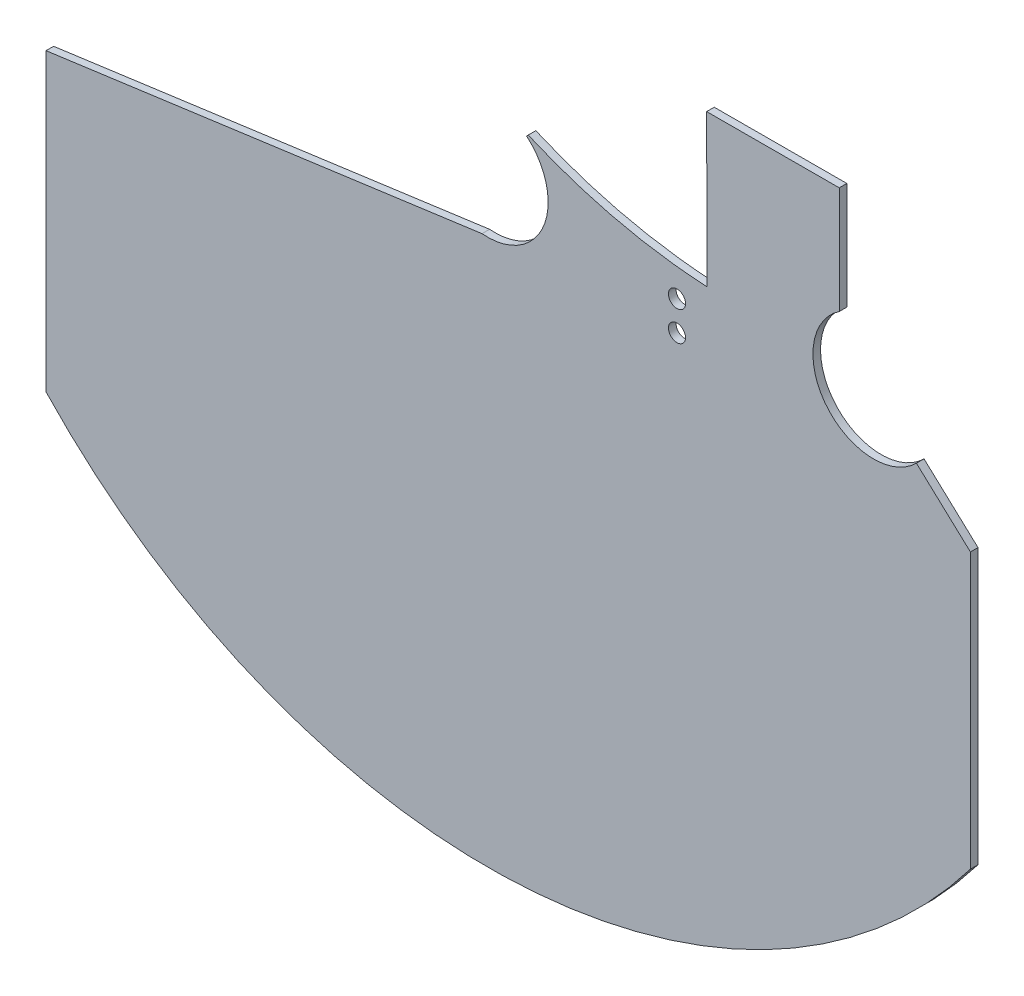
SolidWorks part; units mm, degrees
ref_plane "Front Plane" through (0, 0, 0) normal (0, 0, 1) x (1, 0, 0)
ref_plane "Top Plane" through (0, 0, 0) normal (0, 1, 0) x (1, 0, 0)
ref_plane "Right Plane" through (0, 0, 0) normal (1, 0, 0) x (0, 0, -1)
sketch "Sketch1" plane through (0, 0, 0) normal (0, 0, 1) x (1, 0, 0)
  line L0 (-76.8109, -42.6812) -> (-191.8981, -58.3949)
  line L2 (17.5303, -13.2779) -> (17.466, 14.9412)
  line L3 (-75.0109, -183.6853) -> (-75.0109, -185.6853) construction
  line L5 (-17.534, 14.8615) -> (17.466, 14.9412)
  line L6 (-65.0722, -14.4943) -> (-64.624, -14.0461)
  line L7 (-17.534, 14.8615) -> (-17.4429, -25.1385)
  line L8 (10.3223, 13.4067) -> (7.9165, -10.5732) construction
  line L9 (-83.9257, -51.7428) -> (-126.8973, -177.1633) construction
  line L10 (9.3388, 13.4067) -> (7.549, -10.599) construction
  line L11 (8.3498, 13.4067) -> (7.1746, -10.6299) construction
  line L12 (7.3501, 13.4067) -> (6.7894, -10.6662) construction
  line L13 (-75.305, -51.5878) -> (-75.0109, -180.7466) construction
  line L14 (-75.305, -51.5878) -> (-75.0109, -180.7466) construction
  line L15 (11.2975, 13.4067) -> (8.2735, -10.552) construction
  line L16 (12.2657, 13.4067) -> (8.6199, -10.5347) construction
  line L17 (13.2282, 13.4067) -> (8.9559, -10.5209) construction
  line L18 (14.1861, 13.4067) -> (9.2817, -10.5103) construction
  line L19 (15.1406, 13.4067) -> (9.5974, -10.5024) construction
  line L20 (16.0929, 13.4067) -> (11.113, -5.8245) construction
  line L21 (16.369, 11.049) -> (10.1986, -10.4939) construction
  line L22 (-75.305, -51.5878) -> (-75.0109, -180.7466) construction
  line L23 (16.369, 8.2303) -> (10.4845, -10.4926) construction
  line L24 (16.369, 5.8763) -> (10.7605, -10.493) construction
  line L25 (16.369, 3.887) -> (11.0269, -10.4949) construction
  line L26 (16.369, 2.1893) -> (11.2836, -10.498) construction
  line L27 (16.369, 0.7284) -> (11.5306, -10.5023) construction
  line L28 (16.369, -0.5374) -> (11.7681, -10.5074) construction
  line L29 (16.369, -1.6406) -> (11.996, -10.5133) construction
  line L30 (16.369, -2.6066) -> (12.2142, -10.5199) construction
  line L31 (6.3822, -7.7874) -> (6.3822, -9.7874) construction
  line L32 (-191.8981, -58.8978) -> (-191.8981, -136.3793)
  line L33 (52.0837, -50.9846) -> (52.0837, -123.4821)
  line L34 (-191.8981, -58.8978) -> (-191.8981, -58.3949)
  line L35 (6.3384, 13.4067) -> (6.3822, -5.7874) construction
  line L36 (5.3135, 13.4067) -> (5.9865, -10.7581) construction
  line L38 (4.274, 13.4067) -> (5.5689, -10.8152) construction
  line L39 (3.2185, 13.4067) -> (5.1406, -10.8811) construction
  line L40 (2.1454, 13.4067) -> (4.7018, -10.9568) construction
  line L41 (1.0534, 13.4067) -> (4.2527, -11.0437) construction
  line L42 (-0.0593, 13.4067) -> (3.7937, -11.1432) construction
  line L43 (-1.1943, 13.4067) -> (3.3254, -11.2568) construction
  line L44 (-2.3534, 13.4067) -> (2.8484, -11.3863) construction
  line L45 (-3.5385, 13.4067) -> (2.3637, -11.5339) construction
  line L46 (-4.7516, 13.4067) -> (0.7995, -7.6347) construction
  line L47 (-5.9949, 13.4067) -> (1.3761, -11.8924) construction
  line L48 (-7.2706, 13.4067) -> (0.8766, -12.1088) construction
  line L49 (-8.5813, 13.4067) -> (0.3762, -12.354) construction
  line L50 (-9.9295, 13.4067) -> (-0.1225, -12.6315) construction
  line L51 (-11.3181, 13.4067) -> (-0.6161, -12.9449) construction
  line L52 (52.0837, -50.9846) -> (37.835, -37.8255)
  line L53 (-12.7501, 13.4067) -> (-1.1008, -13.2982) construction
  line L54 (-14.229, 13.4067) -> (-1.5722, -13.6952) construction
  line L55 (-15.7583, 13.4067) -> (-2.0255, -14.1397) construction
  line L56 (-15.7563, 10.4198) -> (-2.4553, -14.6352) construction
  line L57 (-15.7544, 7.6811) -> (-4.9454, -11.4805) construction
  line L58 (-15.7528, 5.1547) -> (-3.2226, -15.7882) construction
  line L59 (-15.7513, 2.8112) -> (-3.5499, -16.447) construction
  line L60 (-15.75, 0.6263) -> (-3.8343, -17.1584) construction
  line L61 (-15.7488, -1.4203) -> (-4.0737, -17.9178) construction
  line L62 (-15.7479, -3.3459) -> (-4.268, -18.7183) construction
  line L63 (-15.7471, -5.1648) -> (-4.4193, -19.5515) construction
  line L64 (-15.7465, -6.8897) -> (-4.5314, -20.4074) construction
  line L65 (-15.7462, -8.5311) -> (-4.6101, -21.2759) construction
  line L66 (-15.746, -10.0983) -> (-4.6618, -22.1477) construction
  line L67 (-15.746, -11.5995) -> (-8.0943, -19.5021) construction
  line L68 (-15.7462, -13.0415) -> (-4.7119, -23.8696) construction
  line L69 (-15.7466, -14.4308) -> (-4.7233, -24.7082) construction
  line L70 (-15.7472, -15.7728) -> (-5.6742, -24.694) construction
  line L71 (-15.748, -17.0723) -> (-6.7037, -24.6789) construction
  line L72 (-15.749, -18.3339) -> (-7.8208, -24.6629) construction
  line L73 (-15.7502, -19.5613) -> (-9.0358, -24.6458) construction
  line L74 (-15.7515, -20.7582) -> (-10.3607, -24.6276) construction
  line L75 (-15.7531, -21.9277) -> (-11.8098, -24.6082) construction
  line L76 (-15.7548, -23.0729) -> (-13.3997, -24.5872) construction
  line L79 (-75.9405, -51.5993) -> (-79.0642, -185.7038) construction
  line L80 (-76.5773, -51.6107) -> (-83.1265, -185.5572) construction
  line L81 (-77.2163, -51.6222) -> (-87.1837, -185.3068) construction
  line L82 (-77.8583, -51.6337) -> (-91.2332, -184.9528) construction
  line L83 (-78.5042, -51.6453) -> (-95.2723, -184.4954) construction
  line L84 (-79.155, -51.657) -> (-99.2984, -183.9348) construction
  line L85 (-79.8114, -51.6688) -> (-103.3089, -183.2716) construction
  line L86 (-80.4745, -51.6808) -> (-107.3011, -182.506) construction
  line L87 (-81.1452, -51.6928) -> (-111.2724, -181.6386) construction
  line L88 (-81.8246, -51.705) -> (-113.9668, -175.8296) construction
  line L89 (-82.5137, -51.7174) -> (-119.1421, -179.6007) construction
  line L90 (-83.2136, -51.73) -> (-123.0352, -178.4316) construction
  line L92 (-84.6511, -51.7558) -> (-130.7256, -175.7967) construction
  line L93 (-85.3911, -51.7691) -> (-134.5177, -174.3327) construction
  line L94 (-86.1474, -51.7827) -> (-138.2712, -172.7722) construction
  line L95 (-86.9213, -51.7967) -> (-141.9836, -171.1163) construction
  line L96 (-87.7146, -51.8109) -> (-145.6524, -169.366) construction
  line L97 (-88.529, -51.8256) -> (-149.2753, -167.5226) construction
  line L98 (-89.3667, -51.8406) -> (-150.4131, -161.221) construction
  line L99 (-90.2296, -51.8561) -> (-156.3738, -163.5608) construction
  line L100 (-91.1202, -51.8721) -> (-159.8448, -161.4451) construction
  line L101 (-92.041, -51.8887) -> (-163.2605, -159.2414) construction
  line L102 (-92.9949, -51.9058) -> (-166.6188, -156.9511) construction
  line L103 (-93.985, -51.9236) -> (-169.9175, -154.5757) construction
  line L104 (-95.0147, -51.9421) -> (-173.1543, -152.1167) construction
  line L105 (-96.088, -51.9614) -> (-176.3273, -149.5758) construction
  line L106 (-97.2091, -51.9816) -> (-179.4342, -146.9547) construction
  line L107 (-98.3829, -52.0027) -> (-182.4732, -144.2549) construction
  line L108 (-99.6148, -52.0248) -> (-181.9804, -137.8705) construction
  line L109 (-100.911, -52.0481) -> (-188.339, -138.6268) construction
  line L110 (-102.2785, -52.0727) -> (-190.8981, -135.4537) construction
  line L111 (-103.7253, -52.0987) -> (-190.8981, -130.0146) construction
  line L112 (-105.2606, -52.1263) -> (-190.8981, -124.8185) construction
  line L113 (-106.895, -52.1557) -> (-190.8981, -119.8432) construction
  line L114 (-108.6406, -52.1871) -> (-190.8981, -115.0689) construction
  line L115 (-110.5118, -52.2207) -> (-190.8981, -110.4776) construction
  line L116 (-112.5255, -52.2569) -> (-190.8981, -106.0534) construction
  line L117 (-114.7014, -52.296) -> (-190.8981, -101.7818) construction
  line L118 (-117.0632, -52.3385) -> (-190.8981, -97.6498) construction
  line L119 (-119.6393, -52.3848) -> (-190.8981, -93.6454) construction
  line L120 (-122.4641, -52.4356) -> (-190.8981, -89.758) construction
  line L121 (-125.5798, -52.4916) -> (-190.8981, -85.9774) construction
  line L122 (-129.0385, -52.5538) -> (-190.8981, -82.2947) construction
  line L123 (-132.9054, -52.6233) -> (-190.8981, -78.7015) construction
  line L124 (-137.2635, -52.7016) -> (-190.8981, -75.1899) construction
  line L125 (-142.2196, -52.7907) -> (-190.8981, -71.7529) construction
  line L126 (-147.9138, -52.8931) -> (-190.8981, -68.3836) construction
  line L127 (-158.5531, -54.3456) -> (-190.8981, -65.0759) construction
  line L128 (-172.5681, -56.2589) -> (-190.8981, -61.8239) construction
  line L133 (-74.6701, -51.5764) -> (-70.935, -185.6853) construction
  line L134 (-74.0348, -51.565) -> (-66.8734, -185.5202) construction
  line L135 (-73.3984, -51.5536) -> (-62.8174, -185.2514) construction
  line L136 (-72.76, -51.5421) -> (-58.7696, -184.8789) construction
  line L137 (-72.1187, -51.5306) -> (-54.7326, -184.4031) construction
  line L138 (-71.4738, -51.519) -> (-50.7091, -183.8242) construction
  line L139 (-70.8242, -51.5073) -> (-46.7017, -183.1426) construction
  line L140 (-70.1692, -51.4955) -> (-42.713, -182.3589) construction
  line L141 (-69.5077, -51.4836) -> (-38.7457, -181.4734) construction
  line L142 (-68.8388, -51.4716) -> (-36.0777, -175.6522) construction
  line L143 (-68.1615, -51.4594) -> (-30.8854, -179.3997) construction
  line L144 (-67.4747, -51.4471) -> (-26.9976, -178.2129) construction
  line L145 (-66.7773, -51.4345) -> (-23.1414, -176.927) construction
  line L146 (-66.0681, -51.4218) -> (-19.3193, -175.543) construction
  line L147 (-65.3459, -51.4088) -> (-15.5339, -174.0617) construction
  line L148 (-64.6093, -51.3956) -> (-11.7875, -172.4842) construction
  line L149 (-63.8569, -51.382) -> (-8.0827, -170.8114) construction
  line L150 (-63.0872, -51.3682) -> (-4.4219, -169.0444) construction
  line L151 (-62.2984, -51.354) -> (-0.8075, -167.1844) construction
  line L152 (-61.489, -51.3395) -> (0.3016, -160.8778) construction
  line L153 (-60.6568, -51.3245) -> (6.2729, -163.1904) construction
  line L154 (-59.7998, -51.3091) -> (9.7342, -161.0589) construction
  line L155 (-58.9157, -51.2932) -> (13.1399, -158.8397) construction
  line L156 (-58.002, -51.2768) -> (16.4877, -156.5341) construction
  line L157 (-57.056, -51.2598) -> (19.7755, -154.1437) construction
  line L158 (-56.0744, -51.2421) -> (23.0011, -151.67) construction
  line L159 (-55.0541, -51.2238) -> (26.1625, -149.1147) construction
  line L160 (-53.9911, -51.2047) -> (29.2574, -146.4794) construction
  line L161 (-52.8813, -51.1847) -> (32.284, -143.7658) construction
  line L162 (-51.72, -51.1639) -> (31.7622, -137.3837) construction
  line L163 (-50.5018, -51.142) -> (38.1242, -138.1111) construction
  line L164 (-49.2208, -51.1189) -> (40.934, -135.1736) construction
  line L165 (-47.8702, -51.0947) -> (43.6678, -132.1652) construction
  line L166 (-46.4423, -51.069) -> (46.3237, -129.0879) construction
  line L167 (-44.928, -51.0418) -> (48.9002, -125.9438) construction
  line L168 (-43.3173, -51.0128) -> (51.0837, -122.4988) construction
  line L169 (-41.5982, -50.9819) -> (51.0837, -117.5078) construction
  line L170 (-39.757, -50.9488) -> (51.0837, -112.6967) construction
  line L171 (-37.7774, -50.9132) -> (51.0837, -108.05) construction
  line L172 (-35.6404, -50.8748) -> (51.0837, -103.5537) construction
  line L173 (-33.3233, -50.8332) -> (51.0837, -99.1949) construction
  line L174 (-30.7989, -50.7878) -> (51.0837, -94.962) construction
  line L175 (-28.0341, -50.7381) -> (51.0837, -90.8443) construction
  line L176 (-24.9889, -50.6833) -> (51.0837, -86.832) construction
  line L177 (-21.6136, -50.6227) -> (51.0837, -82.916) construction
  line L178 (-17.8463, -50.5549) -> (51.0837, -79.088) construction
  line L179 (-13.6086, -50.4788) -> (51.0837, -75.3401) construction
  line L180 (-8.7998, -50.3923) -> (51.0837, -71.6653) construction
  line L181 (-3.2883, -50.2932) -> (51.0837, -68.0565) construction
  line L186 (43.9805, -49.4435) -> (51.0837, -50.7944) construction
  line L189 (30.4462, -49.6868) -> (51.0837, -54.1612) construction
  line L192 (19.5611, -49.8825) -> (51.0837, -57.5655) construction
  line L193 (10.6062, -50.0435) -> (51.0837, -61.0125) construction
  line L194 (3.1008, -50.1784) -> (51.0837, -64.5076) construction
  line L237 (16.6937, -3.6568) -> (9.0919, -16.4949) construction
  line L238 (16.7025, -2.8584) -> (9.0919, -16.4949) construction
  arc A0 (-65.0722, -14.4943) -> (-76.8109, -42.6812) centre (-75.3616, -26.747) cw
  arc A1 (17.5303, -13.2779) -> (37.835, -37.8255) centre (26.5181, -26.5149) ccw
  circle A6 centre (-25.3616, -31.8313) radius 2.25
  circle A7 centre (-25.3616, -39.6213) radius 2.25
  circle A10 centre (26.5181, -26.5149) radius 16 construction
  circle A11 centre (-75.3616, -26.747) radius 16 construction
  arc A13 (-191.8981, -136.3793) -> (52.0837, -123.4821) centre (-75.3616, -26.747) ccw
  spline S2 degree 3 poles (1865.1192, -512.9507) (-249.1616, 189.9136) (-158.2742, 19.2768) (-52.6836, -18.6413) (-44.8961, -20.9333) (187.7258, -74.6464) (546.5182, 472.1899) (1102.3446, 1605.1317) knots -4.449553 -4.449553 -4.449553 -4.449553 0.119867 0.236316 0.352765 0.469214 10.548299 10.548299 10.548299 10.548299 only from (-67.9573, -12.5633) to (-30.3616, -23.8313) construction
  spline S3 degree 3 poles (945.9534, 1654.7166) (-352.081, 486.2678) (-232.2366, -23.7817) (68.2714, -25.9082) (174.051, 40.8175) (-1992.8181, -237.3583) knots -8.518805 -8.518805 -8.518805 -8.518805 0.81856 0.876785 4.185431 4.185431 4.185431 4.185431 only from (-20.3616, -24.9492) to (-4.4406, -25.2547) construction
  spline S6 degree 3 poles (-64.624, -14.0461) (-63.2083, -14.6547) (-59.2353, -16.2885) (-52.6836, -18.6413) (-44.8961, -20.9333) (-33.2641, -23.6191) (-24.0616, -24.7787) (-17.4429, -25.1385) knots 0.05479 0.05479 0.05479 0.05479 0.119867 0.236316 0.352765 0.469214 0.751954 0.751954 0.751954 0.751954
  spline S7 degree 3 poles (-19.2221, -25.0302) (-18.6298, -25.0698) (-18.0368, -25.1058) (-17.4429, -25.138) knots 0.726554 0.726554 0.726554 0.726554 0.751906 0.751906 0.751906 0.751906
  point P42 (-75.3616, -26.747)
  dimension "D1" = 4.5
  dimension "D2" = 4.5
  dimension "D11" = 43
  dimension "D12" = 16
  dimension "D7" = 160
  dimension "D10" = 22
  dimension "D4" = 19.3956
  dimension "D6" = 17.5
  dimension "D9" = 19
  dimension "D14" = 11
  dimension "D18" = 2
  dimension "D19" = 2
extrude "Boss-Extrude1" add sketch "Sketch1" along normal blind 2
